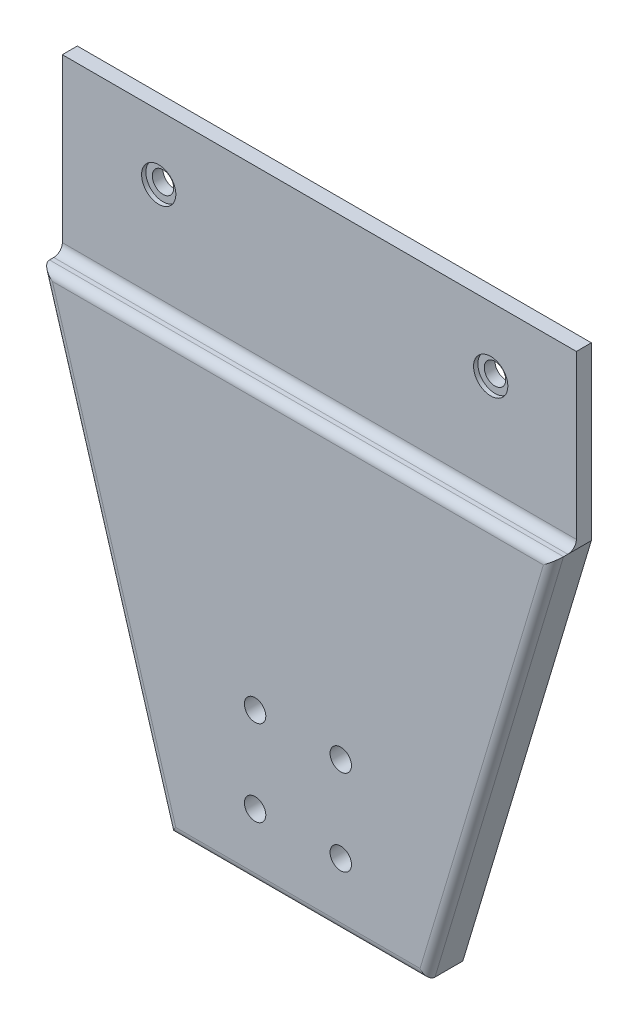
SolidWorks part; units mm, degrees
ref_plane "Front Plane" through (0, 0, 0) normal (0, 0, 1) x (1, 0, 0)
ref_plane "Top Plane" through (0, 0, 0) normal (0, 1, 0) x (1, 0, 0)
ref_plane "Right Plane" through (0, 0, 0) normal (1, 0, 0) x (0, 0, -1)
sketch "Sketch1" plane through (0, 0, 0) normal (0, 0, 1) x (1, 0, 0)
  line L2 (228.6, -311.15) -> (190.5, -438.15)
  line L3 (190.5, -438.15) -> (114.3, -438.15)
  line L4 (76.2, -311.15) -> (114.3, -438.15)
  line L5 (152.4, -438.15) -> (152.4, -295.3263) construction
  line L6 (228.6, -311.15) -> (76.2, -311.15)
  line L7 (2.413, -304.8) -> (302.387, -304.8) construction
  line L8 (152.4, -1.3335) -> (152.4, -8.3185) construction
  point P11 (152.4, -311.15)
  dimension "D1" = 6.35
  dimension "D2" = 76.2
  dimension "D3" = 127
  dimension "D4" = 152.4
extrude "Boss-Extrude1" add sketch "Sketch1" against normal blind 10.795
sketch "Sketch2" plane through (0, -311.15, 0) normal (0, 1, 0) x (1, 0, 0)
  line L0 (228.6, 10.795) -> (76.2, 10.795) construction
  line L1 (76.2, 10.795) -> (228.6, 10.795)
  line L2 (76.2, 10.795) -> (76.2, 6.35)
  line L3 (76.2, 6.35) -> (228.6, 6.35)
  line L4 (228.6, 10.795) -> (228.6, 6.35)
  line L6 (206.6925, 6.35) -> (199.7075, 6.35) construction
extrude "Boss-Extrude2" add sketch "Sketch2" along normal blind 50.8
sketch "Sketch3" plane through (0, 0, -10.795) normal (0, 0, -1) x (-1, 0, 0)
  line L0 (-76.2, -260.35) -> (-76.2, -311.15) construction
  line L2 (-228.6, -260.35) -> (-76.2, -260.35) construction
  line L3 (-228.6, -260.35) -> (-228.6, -311.15) construction
  circle A0 centre (-104.775, -279.4) radius 3.175
  circle A1 centre (-203.2, -279.4) radius 3.175
  circle A2 centre (-139.7, -393.7) radius 3.175
  circle A3 centre (-165.1, -393.7) radius 3.175
  circle A4 centre (-139.7, -419.1) radius 3.175
  circle A5 centre (-165.1, -419.1) radius 3.175
  dimension "D1" = 6.35
  dimension "D3" = 19.05
  dimension "D2" = 25.4
  dimension "D4" = 25.4
extrude "Cut-Extrude1" cut sketch "Sketch3" against normal through all
fillet "Fillet1" radius 2.54 1 edges at (152.4, -311.15, -6.35)
fillet "Fillet2" radius 2.54 4 edges at (152.4, -438.15, 0) (95.25, -374.65, 0) (152.4, -311.15, 0) (209.55, -374.65, 0)
sketch "Sketch4" plane through (0, 0, -6.35) normal (0, 0, 1) x (1, 0, 0)
  circle A0 centre (104.775, -279.4) radius 5.08
  circle A1 centre (203.2, -279.4) radius 5.08
  dimension "D1" = 10.16
  dimension "D2" = 10.16
extrude "Cut-Extrude2" cut sketch "Sketch4" against normal blind 1.27
equation "\"D2@Sketch4\"=\"D1@Sketch4\""
